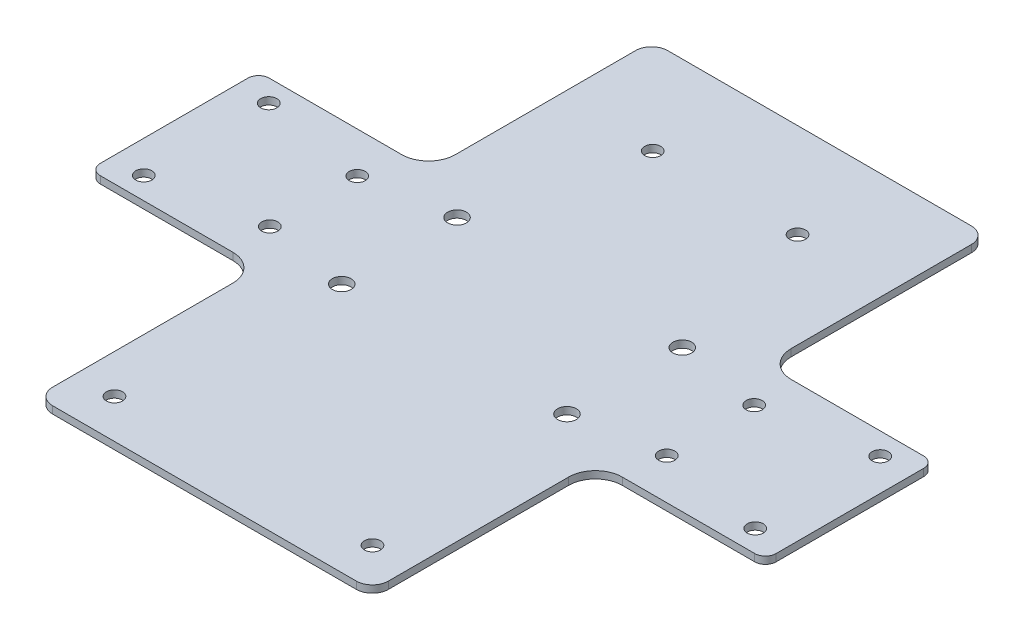
SolidWorks part; units mm, degrees
material "Acrylic (Medium-high impact)"
ref_plane "Front Plane" through (0, 0, 0) normal (0, 0, 1) x (1, 0, 0)
ref_plane "Top Plane" through (0, 0, 0) normal (0, 1, 0) x (1, 0, 0)
ref_plane "Right Plane" through (0, 0, 0) normal (1, 0, 0) x (0, 0, -1)
sketch "Sketch1" plane through (0, 0, 0) normal (0, 1, 0) x (1, 0, 0)
  line L0 (64, -14.75) -> (64, 14.75) construction
  line L1 (-64, 14.75) -> (-64, -14.75) construction
  line L2 (64, -14.75) -> (64, 14.75)
  line L3 (-64, 14.75) -> (-64, -14.75)
  line L4 (0, 39.7351) -> (0, -50.0649) construction
  line L5 (-27.305, 53.34) -> (27.305, 53.34)
  line L6 (-27.305, 53.34) -> (-27.305, -53.34)
  line L7 (-27.305, -53.34) -> (27.305, -53.34)
  line L8 (27.305, 53.34) -> (27.305, -53.34)
  line L9 (-27.305, 53.34) -> (27.305, -53.34) construction
  line L10 (-27.305, -53.34) -> (27.305, 53.34) construction
  line L11 (-13.5, 39.7351) -> (13.5, 39.7351) construction
  line L12 (-24.05, -50.0649) -> (24.05, -50.0649) construction
  line L13 (24.05, -50.0649) -> (27.305, -53.34) construction
  line L14 (-64, 15.75) -> (64, 15.75) construction
  line L15 (-64, -15.75) -> (64, -15.75) construction
  line L16 (-104.5, 15.75) -> (104.5, 15.75) construction
  line L17 (-104.5, -15.75) -> (104.5, -15.75) construction
  circle A0 centre (-13.5, 39.7351) radius 1
  circle A1 centre (-37, -8.15) radius 1.6
  circle A2 centre (-37, -8.15) radius 1.6
  circle A3 centre (-57, 11.65) radius 1.6
  circle A4 centre (-57, 11.65) radius 1.6
  circle A5 centre (-57, -11.65) radius 1.6
  circle A6 centre (-57, -11.65) radius 1.6
  circle A7 centre (-37, 8.15) radius 1.6
  circle A8 centre (-37, 8.15) radius 1.6
  circle A9 centre (37, 8.15) radius 1.6
  circle A10 centre (37, 8.15) radius 1.6
  circle A11 centre (57, -11.65) radius 1.6
  circle A12 centre (57, -11.65) radius 1.6
  circle A13 centre (57, 11.65) radius 1.6
  circle A14 centre (57, 11.65) radius 1.6
  circle A15 centre (37, -8.15) radius 1.6
  circle A16 centre (37, -8.15) radius 1.6
  circle A17 centre (13.5, 39.7351) radius 1
  circle A18 centre (-24.05, -50.0649) radius 1
  circle A19 centre (24.05, -50.0649) radius 1
  point P28 (0, 0)
  point P38 (0, 39.7351)
  point P41 (0, -50.0649)
  dimension "D11" = 2
  dimension "D9" = 54.61
  dimension "D10" = 106.68
  dimension "D12" = 89.8
  dimension "D13" = 48.1
  dimension "D14" = 27
  dimension "D15" = 4.6175
  dimension "D1" = 0
  dimension "D2" = 0
  dimension "D3" = 0
  dimension "D4" = 0
  dimension "D5" = 0
  dimension "D6" = 0
  dimension "D7" = 0
  dimension "D8" = 0
sketch "Sketch3" plane through (0, 0, 0) normal (0, 1, 0) x (1, 0, 0)
  line L0 (31.305, 15.75) -> (31.305, 57.34)
  line L4 (-63, 15.75) -> (-63, -15.75)
  line L5 (-64, 14.75) -> (-64, -14.75) construction
  line L6 (-64, 14.75) -> (-64, -14.75) construction
  line L7 (-63, 15.75) -> (-31.305, 15.75)
  line L8 (-31.305, -57.34) -> (31.305, -57.34)
  line L9 (31.305, -57.34) -> (31.305, 57.34)
  line L10 (31.305, 57.34) -> (-31.305, 57.34)
  line L11 (-31.305, 57.34) -> (-31.305, -57.34)
  line L12 (-31.305, -57.34) -> (31.305, -57.34)
  line L13 (31.305, -57.34) -> (31.305, -15.75)
  line L14 (31.305, 57.34) -> (-31.305, 57.34)
  line L15 (-31.305, 57.34) -> (-31.305, 15.75)
  line L16 (-63, -15.75) -> (-31.305, -15.75)
  line L17 (-64, 15.75) -> (64, 15.75) construction
  line L18 (0, 39.7351) -> (0, -50.0649) construction
  line L19 (0, 39.7351) -> (0, -50.0649) construction
  line L20 (63, -15.75) -> (31.305, -15.75)
  line L21 (63, 15.75) -> (63, -15.75)
  line L22 (63, 15.75) -> (31.305, 15.75)
  line L23 (-31.305, -15.75) -> (-31.305, -57.34)
  circle A8 centre (-57, 11.65) radius 1.5
  circle A9 centre (-57, -11.65) radius 1.5
  circle A10 centre (-37, -8.15) radius 1.5
  circle A11 centre (-37, 8.15) radius 1.5
  circle A12 centre (37, 8.15) radius 1.5
  circle A13 centre (57, 11.65) radius 1.5
  circle A14 centre (57, -11.65) radius 1.5
  circle A15 centre (37, -8.15) radius 1.5
  circle A16 centre (-13.5, 39.7351) radius 1.5
  circle A17 centre (13.5, 39.7351) radius 1.5
  circle A18 centre (-24.05, -50.0649) radius 1.5
  circle A19 centre (24.05, -50.0649) radius 1.5
  point P36 (-64, 0)
  point P41 (-63, 0)
  dimension "D1" = 3
  dimension "D3" = 1
  dimension "D2" = 4
extrude "Boss-Extrude1" add sketch "Sketch3" along normal blind 1.35
fillet "Fillet1" radius 2 4 edges at (-63, 0.675, -15.75) (63, 0.675, -15.75) (63, 0.675, 15.75) (-63, 0.675, 15.75)
fillet "Fillet2" radius 3 4 edges at (-31.305, 0.675, -57.34) (31.305, 0.675, -57.34) (31.305, 0.675, 57.34) (-31.305, 0.675, 57.34)
fillet "Fillet3" radius 5 4 edges at (-31.305, 0.675, -15.75) (-31.305, 0.675, 15.75) (31.305, 0.675, -15.75) (31.305, 0.675, 15.75)
sketch "Sketch4" plane through (0, 1.35, 0) normal (0, 1, 0) x (1, 0, 0)
  circle A1 centre (-21, -10.75) radius 1.75
  circle A2 centre (-21, -10.75) radius 1.75
  circle A3 centre (21, -10.75) radius 1.75
  circle A4 centre (21, -10.75) radius 1.75
  circle A5 centre (21, 10.75) radius 1.75
  circle A6 centre (21, 10.75) radius 1.75
  circle A7 centre (-21, 10.75) radius 1.75
  circle A8 centre (-21, 10.75) radius 1.75
  dimension "D1" = 0
  dimension "D2" = 0
  dimension "D3" = 0
  dimension "D4" = 0
extrude "Cut-Extrude1" cut sketch "Sketch4" against normal through all
equation "\"Black_acrylic\"= 1.35mm"
